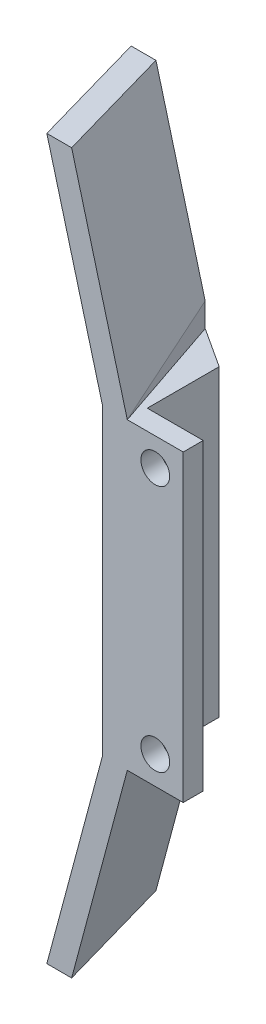
SolidWorks part; units mm, degrees
ref_plane "Plan de face" through (0, 0, 0) normal (0, 0, 1) x (1, 0, 0)
ref_plane "Plan de dessus" through (0, 0, 0) normal (0, 1, 0) x (1, 0, 0)
ref_plane "Plan de droite" through (0, 0, 0) normal (1, 0, 0) x (0, 0, -1)
ref_plane "Plan5" through (0, 0, -14.75) normal (0, 0, 1) x (1, 0, 0)
sketch "Esquisse11" plane through (0, 0, -14.75) normal (0, 0, 1) x (1, 0, 0)
  line L0 (-11.1628, 45) -> (-14.2687, 45)
  line L1 (-14.2687, 45) -> (-8.1058, 22)
  line L2 (-8.1058, 22) -> (-8.1058, -22)
  line L3 (-11.1628, 45) -> (-5, 22)
  line L4 (-5, 22) -> (-5, -22)
  line L7 (-11.1628, -45) -> (-5, -22)
  line L8 (-14.2687, -45) -> (-8.1058, -22)
  line L9 (-11.1628, -45) -> (-14.2687, -45)
  point P12 (-5, 0)
  point P14 (-8.1058, 0)
  dimension "D2" = 44
  dimension "D3" = 44
  dimension "D4" = 165
  dimension "D5" = 165
  dimension "D6" = 90
  dimension "D14" = 3
  dimension "D15" = 3
  dimension "D16" = 5
  dimension "D17" = 22
sketch "Esquisse12" plane through (0, 0, 0) normal (0, 0, -1) x (-1, 0, 0)
  line L0 (0, -19) -> (0, 19)
  line L24 (3.1058, 19) -> (10.0725, 45)
  line L25 (10.0725, 45) -> (6.9667, 45)
  line L26 (6.9667, 45) -> (0, 19)
  line L32 (0, -19) -> (6.9667, -45)
  line L33 (6.9667, -45) -> (10.0725, -45)
  line L34 (10.0725, -45) -> (3.1058, -19)
  line L35 (3.1058, -19) -> (3.1058, 19)
  dimension "D2" = 38
  dimension "D3" = 165
  dimension "D4" = 38
  dimension "D5" = 165
  dimension "D1" = 3
  dimension "D6" = 90
  dimension "D8" = 3
loft "Lissage4" add profiles "Esquisse12", "Esquisse11"
sketch "Esquisse10" plane through (0, 0, 0) normal (0, 0, 1) x (1, 0, 0)
  line L0 (0, 19) -> (0, -19) construction
  line L1 (-3.1058, 19) -> (7, 19)
  line L3 (-3.1058, 19) -> (-3.1058, -19)
  line L4 (-3.1058, -19) -> (7, -19)
  line L5 (7, 19) -> (7, -19)
  dimension "D1" = 7
extrude "Boss.-Extru.1" add sketch "Esquisse10" against normal blind 2.5 separate body
ref_plane "Plan6" through (0, 0, 0) normal (1, 0, 0) x (0, 0, -1)
sketch "Esquisse13" plane through (0, 0, 0) normal (0, 0, 1) x (1, 0, 0)
  line L0 (3.5, 15.5) -> (3.5, -15.5) construction
  line L1 (0, 0) -> (7, 0) construction
  line L2 (7, -19) -> (7, 19) construction
  line L3 (7, 19) -> (-3.1058, 19) construction
  circle A0 centre (3.5, 15.5) radius 1.8
  circle A2 centre (3.5, -15.5) radius 1.8
  point P8 (3.5, 0)
  point P11 (3.5, 0)
  dimension "D1" = 3.6
  dimension "D2" = 3.5
extrude "Enlèv. mat.-Extru.1" cut sketch "Esquisse13" against normal up to next (2.5 mm away)
sketch "Esquisse16" plane through (0, 0, 0) normal (1, 0, 0) x (0, 0, -1)
  line L1 (2.5, -19) -> (11.5, -19)
  line L2 (2.5, -19) -> (2.5, 19)
  line L3 (2.5, 19) -> (11.5, 19)
  line L4 (11.5, -19) -> (11.5, 19)
  dimension "D1" = 9
extrude "Boss.-Extru.2" add sketch "Esquisse16" against normal up to next
sketch "Esquisse17" plane through (0, 0, 0) normal (0, 1, 0) x (1, 0, 0)
  line L0 (0, 11.5) -> (-5, 14.75)
rib "Nervure3" sketch "Esquisse17" sketch "Esquisse17" thickness 38 extrusion direction parallel to sketch draft on no parameters "D1"=38
